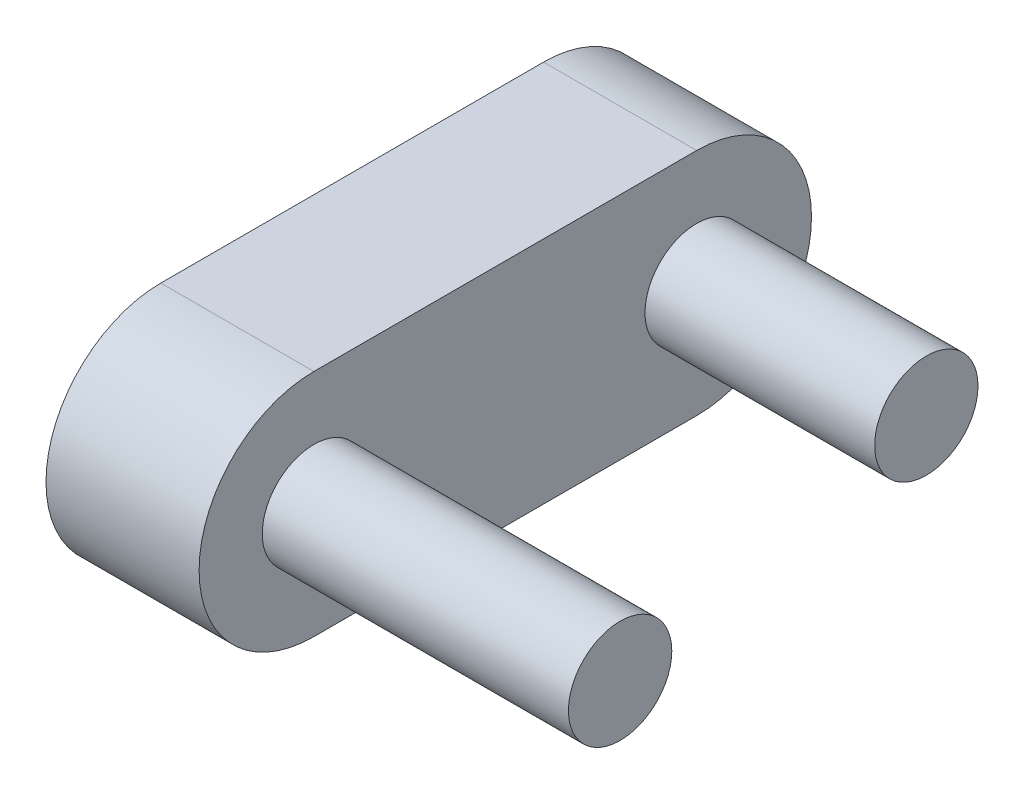
SolidWorks part; units mm, degrees
ref_plane "Front Plane" through (0, 0, 0) normal (0, 0, 1) x (1, 0, 0)
ref_plane "Top Plane" through (0, 0, 0) normal (0, 1, 0) x (1, 0, 0)
ref_plane "Right Plane" through (0, 0, 0) normal (1, 0, 0) x (0, 0, -1)
sketch "Sketch1" plane through (0, 0, 0) normal (1, 0, 0) x (0, 0, -1)
  line L0 (-2.5, 0) -> (2.5, 0) construction
  line L1 (5.5, 0) -> (-5.5, 0) construction
  line L2 (0, 1.65) -> (0, -1.65) construction
  line L3 (-2.5, 1.5) -> (2.5, 1.5)
  line L4 (2.5, -1.5) -> (-2.5, -1.5)
  arc A0 (-2.5, 1.5) -> (-2.5, -1.5) centre (-2.5, 0) ccw
  arc A1 (2.5, 1.5) -> (2.5, -1.5) centre (2.5, 0) cw
  point P12 (2.5, 0)
  point P13 (-2.5, 0)
  dimension "D3" = 1.5
  dimension "D1" = 5
  dimension "D2" = 2.5
extrude "Boss-Extrude1" add sketch "Sketch1" along normal mid plane 2
sketch "Sketch2" plane through (0, 0, 0) normal (1, 0, 0) x (0, 0, -1)
  circle A0 centre (-2.5, 0) radius 0.675
  dimension "D1" = 1.35
sketch "Sketch3" plane through (0, 0, 0) normal (1, 0, 0) x (0, 0, -1)
  circle A0 centre (2.5, 0) radius 0.675
  dimension "D1" = 1.35
extrude "Boss-Extrude2" add sketch "Sketch2" along normal blind 5
extrude "Boss-Extrude3" add sketch "Sketch3" along normal blind 4
